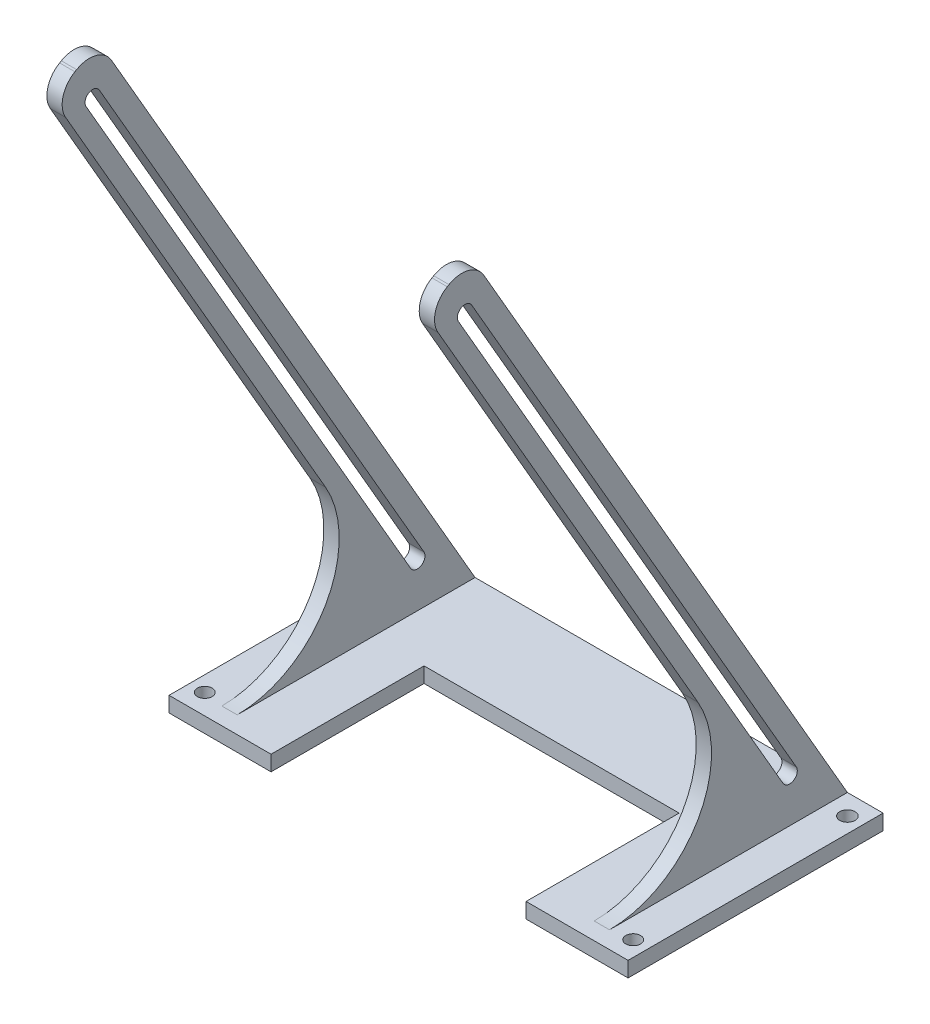
SolidWorks part; units mm, degrees
ref_plane "前视基准面" through (0, 0, 0) normal (0, 0, 1) x (1, 0, 0)
ref_plane "上视基准面" through (0, 0, 0) normal (0, 1, 0) x (1, 0, 0)
ref_plane "右视基准面" through (0, 0, 0) normal (1, 0, 0) x (0, 0, -1)
other "Configuration Table"
sketch "草图1" plane through (0, 0, 0) normal (0, 1, 0) x (1, 0, 0)
  line L0 (0, 0) -> (-35, 0)
  line L1 (-35, 0) -> (-35, -30)
  line L2 (-35, -30) -> (-45, -30)
  line L3 (-45, -30) -> (-45, 20)
  line L4 (-45, 20) -> (45, 20)
  line L5 (45, 20) -> (45, -30)
  line L6 (45, -30) -> (35, -30)
  line L7 (35, -30) -> (35, 0)
  line L8 (35, 0) -> (0, 0)
  line L9 (0, 48.9867) -> (0, -43.8879) construction
  line L10 (-42, 16) -> (-42, -26.8808) construction
  circle A0 centre (-42, -26) radius 1.4484
  circle A1 centre (-42, 16) radius 1.5
  circle A2 centre (42, -26) radius 1.4484
  circle A3 centre (42, 16) radius 1.5
  dimension "D5" = 3
  dimension "D6" = 4
  dimension "D7" = 3
  dimension "D1" = 35
  dimension "D2" = 10
  dimension "D3" = 50
  dimension "D4" = 30
  dimension "D8" = 4
extrude "凸台-拉伸1" add sketch "草图1" along normal blind 3
sketch "草图2" plane through (-35, 0, 0) normal (1, 0, 0) x (0, 0, -1)
  line L0 (-9.3205, 33) -> (-60.2827, 121.2691)
  line L1 (-58.4525, 128.0992) -> (-58.1128, 128.2953)
  line L2 (-51.2827, 126.4652) -> (20, 3)
  line L3 (-54.9723, 121.8558) -> (8.6781, 11.6102) construction
  line L4 (-53.6733, 122.6058) -> (9.9771, 12.3602)
  line L5 (-56.2713, 121.1058) -> (7.379, 10.8602)
  line L6 (-30, 3) -> (20, 3) construction
  line L7 (20, 3) -> (8, 3)
  line L8 (20, 3) -> (-30, 3) construction
  line L9 (8, 3) -> (-26.641, 3)
  arc A0 (-53.6733, 122.6058) -> (-56.2713, 121.1058) centre (-54.9723, 121.8558) ccw
  arc A1 (7.379, 10.8602) -> (9.9771, 12.3602) centre (8.6781, 11.6102) ccw
  arc A2 (-51.2827, 126.4652) -> (-58.1128, 128.2953) centre (-55.6128, 123.9652) ccw
  arc A3 (-60.2827, 121.2691) -> (-58.4525, 128.0992) centre (-55.9525, 123.7691) cw
  arc A4 (-26.641, 3) -> (-9.3205, 33) centre (-26.641, 23) ccw
  point P8 (-23.1471, 66.733)
  dimension "D4" = 5
  dimension "D1" = 3
  dimension "D2" = 4
  dimension "D3" = 60
  dimension "D5" = 12
  dimension "D6" = 20
extrude "凸台-拉伸2" add sketch "草图2" against normal blind 3 contours A3 L0 L7 L2 A2 L1 A1 L5 A0 L4
mirror "镜向1" about plane through (0, 0, 0) normal (1, 0, 0) of "凸台-拉伸2"
sketch "草图5" plane through (0, 0, 0) normal (0, -1, 0) x (1, 0, 0)
  line L0 (-35, 0) -> (35, 0) construction
  line L1 (-35, 30) -> (-25, 30)
  line L2 (-35, 30) -> (-35, 0)
  line L3 (-35, 0) -> (-25, 0)
  line L4 (-25, 30) -> (-25, 0)
  line L6 (35, 30) -> (25, 30)
  line L7 (35, 30) -> (35, 0)
  line L8 (35, 0) -> (25, 0)
  line L9 (25, 30) -> (25, 0)
  dimension "D1" = 10
  dimension "D2" = 10
extrude "凸台-拉伸3" add sketch "草图5" against normal blind 3
